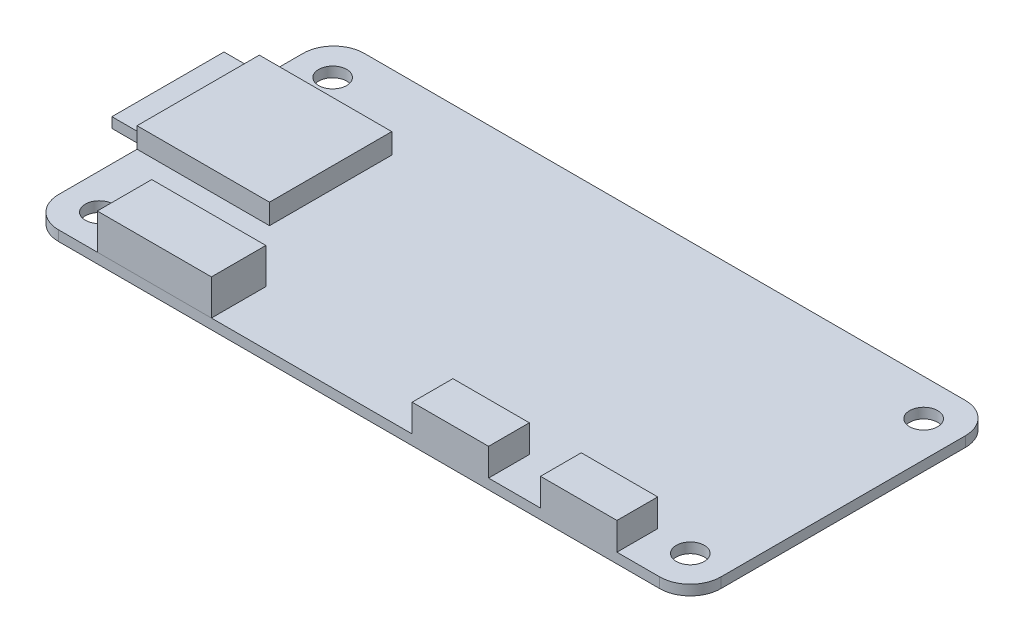
SolidWorks part; units mm, degrees
ref_plane "前视基准面" through (0, 0, 0) normal (0, 0, 1) x (1, 0, 0)
ref_plane "上视基准面" through (0, 0, 0) normal (0, 1, 0) x (1, 0, 0)
ref_plane "右视基准面" through (0, 0, 0) normal (1, 0, 0) x (0, 0, -1)
sketch "zero" plane through (0, 0, 0) normal (0, 1, 0) x (1, 0, 0)
  line L1 (-29.5, 15) -> (29.5, 15)
  line L2 (-32.5, 12) -> (-32.5, -12)
  line L3 (-29.5, -15) -> (29.5, -15)
  line L4 (32.5, 12) -> (32.5, -12)
  line L5 (-32.5, 15) -> (32.5, -15) construction
  line L6 (-32.5, -15) -> (32.5, 15) construction
  line L7 (-25.7, -15) -> (-14.5, -15)
  line L8 (-25.7, -15) -> (-25.7, -9.6569)
  line L9 (-25.7, -9.6569) -> (-14.5, -9.6569)
  line L10 (-14.5, -15) -> (-14.5, -9.6569)
  line L11 (5.2, -15) -> (12.7, -15)
  line L12 (5.2, -15) -> (5.2, -11)
  line L13 (5.2, -11) -> (12.7, -11)
  line L14 (12.7, -15) -> (12.7, -11)
  line L15 (17.8, -15) -> (25.3, -15)
  line L16 (17.8, -15) -> (17.8, -11)
  line L17 (17.8, -11) -> (25.3, -11)
  line L18 (25.3, -15) -> (25.3, -11)
  line L19 (-32.5, 7.7) -> (-19.5, 7.7)
  line L20 (-32.5, 7.7) -> (-32.5, -4.3)
  line L21 (-32.5, -4.3) -> (-19.5, -4.3)
  line L22 (-19.5, 7.7) -> (-19.5, -4.3)
  line L23 (-25.5, 14) -> (25.5, 14)
  line L24 (-25.5, 14) -> (-25.5, 8.8)
  line L25 (-25.5, 8.8) -> (25.5, 8.8)
  line L26 (25.5, 14) -> (25.5, 8.8)
  line L27 (-19.5, 7.2329) -> (-35.5, 7.2329)
  line L28 (-19.5, 7.2329) -> (-19.5, -3.7671)
  line L29 (-19.5, -3.7671) -> (-35.5, -3.7671)
  line L30 (-35.5, 7.2329) -> (-35.5, -3.7671)
  arc A0 (29.5, -15) -> (32.5, -12) centre (29.5, -12) ccw
  arc A1 (29.5, 15) -> (32.5, 12) centre (29.5, 12) cw
  arc A2 (-32.5, -12) -> (-29.5, -15) centre (-29.5, -12) ccw
  arc A3 (-29.5, 15) -> (-32.5, 12) centre (-29.5, 12) ccw
  circle A4 centre (-29, 11.4) radius 3
  circle A5 centre (-29, -11.5) radius 3
  circle A6 centre (29, 11.4) radius 3
  circle A7 centre (29, -11.5) radius 3
  circle A8 centre (-29, 11.4) radius 1.375
  circle A9 centre (-29, -11.5) radius 1.375
  circle A10 centre (29, -11.5) radius 1.375
  circle A11 centre (29, 11.4) radius 1.375
  point P0 (0, 0)
  dimension "D3" = 3
  dimension "D4" = 6
  dimension "D9" = 2.75
  dimension "D1" = 65
  dimension "D2" = 30
  dimension "D5" = 3.6
  dimension "D6" = 3.5
  dimension "D7" = 3.5
  dimension "D8" = 3.5
  dimension "D10" = 12
  dimension "D11" = 7.3
  dimension "D12" = 13
  dimension "D13" = 11.2
  dimension "D14" = 6.8
  dimension "D15" = 19.7
  dimension "D16" = 7.5
  dimension "D17" = 7.5
  dimension "D18" = 5.1
  dimension "D19" = 4
  dimension "D20" = 5.2
  dimension "D21" = 7
  dimension "D22" = 7
  dimension "D23" = 1
  dimension "D24" = 11
  dimension "D25" = 16
sketch "sugar" plane through (0, 0, 0) normal (0, 1, 0) x (1, 0, 0)
  line L1 (-29.5, 15) -> (29.5, 15)
  line L2 (-32.5, 12) -> (-32.5, -12)
  line L3 (-29.5, -15) -> (29.5, -15)
  line L4 (32.5, 12) -> (32.5, -12)
  line L5 (-32.5, 15) -> (32.5, -15) construction
  line L6 (-32.5, -15) -> (32.5, 15) construction
  line L7 (23.5, -11.5) -> (19.5, -11.5)
  line L8 (23.5, -11.5) -> (23.5, -13.9082)
  line L9 (23.5, -13.9082) -> (19.5, -13.9082)
  line L10 (19.5, -11.5) -> (19.5, -13.9082)
  line L11 (16, -11.0071) -> (8.5, -11.0071)
  line L12 (16, -11.0071) -> (16, -15)
  line L13 (16, -15) -> (8.5, -15)
  line L14 (8.5, -11.0071) -> (8.5, -15)
  line L15 (20.5, -13.9082) -> (22.5, -13.9082)
  line L16 (20.5, -13.9082) -> (20.5, -14.8173)
  line L17 (20.5, -14.8173) -> (22.5, -14.8173)
  line L18 (22.5, -13.9082) -> (22.5, -14.8173)
  arc A0 (29.5, 15) -> (32.5, 12) centre (29.5, 12) cw
  arc A1 (29.5, -15) -> (32.5, -12) centre (29.5, -12) ccw
  arc A2 (-32.5, -12) -> (-29.5, -15) centre (-29.5, -12) ccw
  arc A3 (-29.5, 15) -> (-32.5, 12) centre (-29.5, 12) ccw
  circle A4 centre (-29, 11.4) radius 3
  circle A5 centre (-29, 11.4) radius 1.375
  circle A6 centre (-29, -11.5) radius 3
  circle A7 centre (-29, -11.5) radius 1.375
  circle A8 centre (29, 11.4) radius 3
  circle A9 centre (29, 11.4) radius 1.375
  circle A10 centre (29, -11.5) radius 3
  circle A11 centre (29, -11.5) radius 1.375
  dimension "D3" = 3
  dimension "D1" = 65
  dimension "D2" = 30
  dimension "D4" = 9
  dimension "D5" = 4
  dimension "D6" = 3.5
  dimension "D7" = 7.5
  dimension "D8" = 2
  dimension "D9" = 1
sketch "草图1" plane through (0, 0, 0) normal (0, 1, 0) x (1, 0, 0)
  line L4 (-32.5, 12) -> (-32.5, -12)
  line L5 (-29.5, -15) -> (29.5, -15)
  line L6 (32.5, -12) -> (32.5, 12)
  line L7 (29.5, 15) -> (-29.5, 15)
  line L8 (-32.5, 12) -> (-32.5, -12)
  line L9 (-29.5, -15) -> (29.5, -15)
  line L10 (32.5, -12) -> (32.5, 12)
  line L11 (29.5, 15) -> (-29.5, 15)
  circle A1 centre (29, 11.4) radius 1.375
  circle A2 centre (29, 11.4) radius 1.375
  circle A3 centre (29, -11.5) radius 1.375
  circle A4 centre (29, -11.5) radius 1.375
  circle A5 centre (-29, -11.5) radius 1.375
  circle A6 centre (-29, -11.5) radius 1.375
  circle A7 centre (-29, 11.4) radius 1.375
  circle A8 centre (-29, 11.4) radius 1.375
  arc A20 (-32.5, -12) -> (-29.5, -15) centre (-29.5, -12) ccw
  arc A21 (29.5, -15) -> (32.5, -12) centre (29.5, -12) ccw
  arc A22 (32.5, 12) -> (29.5, 15) centre (29.5, 12) ccw
  arc A23 (-29.5, 15) -> (-32.5, 12) centre (-29.5, 12) ccw
  arc A24 (-32.5, -12) -> (-29.5, -15) centre (-29.5, -12) ccw
  arc A25 (29.5, -15) -> (32.5, -12) centre (29.5, -12) ccw
  arc A26 (32.5, 12) -> (29.5, 15) centre (29.5, 12) ccw
  arc A27 (-29.5, 15) -> (-32.5, 12) centre (-29.5, 12) ccw
  dimension "D1" = 0
  dimension "D2" = 0
  dimension "D3" = 0
  dimension "D4" = 0
  dimension "D9" = 0
extrude "凸台-拉伸1" add sketch "草图1" along normal blind 1
ref_plane "基准面1" through (0, 1, 0) normal (0, 1, 0) x (1, 0, 0)
sketch "草图2" plane through (0, 1, 0) normal (0, 1, 0) x (1, 0, 0)
  line L20 (17.8, -15) -> (25.3, -15)
  line L21 (25.3, -15) -> (25.3, -11)
  line L22 (25.3, -11) -> (17.8, -11)
  line L23 (17.8, -11) -> (17.8, -15)
  line L24 (17.8, -15) -> (25.3, -15)
  line L25 (25.3, -15) -> (25.3, -11)
  line L26 (25.3, -11) -> (17.8, -11)
  line L27 (17.8, -11) -> (17.8, -15)
  line L28 (5.2, -15) -> (12.7, -15)
  line L29 (12.7, -15) -> (12.7, -11)
  line L30 (12.7, -11) -> (5.2, -11)
  line L31 (5.2, -11) -> (5.2, -15)
  line L32 (5.2, -15) -> (12.7, -15)
  line L33 (12.7, -15) -> (12.7, -11)
  line L34 (12.7, -11) -> (5.2, -11)
  line L35 (5.2, -11) -> (5.2, -15)
  dimension "D11" = 0
  dimension "D12" = 0
extrude "凸台-拉伸2" add sketch "草图2" along normal blind 2.7
sketch "草图3" plane through (0, 1, 0) normal (0, 1, 0) x (1, 0, 0)
  line L36 (-25.7, -15) -> (-14.5, -15)
  line L37 (-25.7, -9.6569) -> (-25.7, -15)
  line L38 (-14.5, -9.6569) -> (-25.7, -9.6569)
  line L39 (-14.5, -15) -> (-14.5, -9.6569)
  line L40 (-25.7, -15) -> (-14.5, -15)
  line L41 (-25.7, -9.6569) -> (-25.7, -15)
  line L42 (-14.5, -9.6569) -> (-25.7, -9.6569)
  line L43 (-14.5, -15) -> (-14.5, -9.6569)
  dimension "D13" = 0
extrude "凸台-拉伸3" add sketch "草图3" along normal blind 3.5 separate body
sketch "草图4" plane through (0, 1, 0) normal (0, 1, 0) x (1, 0, 0)
  line L12 (-19.5, 7.7) -> (-32.5, 7.7)
  line L13 (-19.5, -4.3) -> (-19.5, 7.7)
  line L14 (-32.5, -4.3) -> (-19.5, -4.3)
  line L15 (-32.5, 7.7) -> (-32.5, -4.3)
  line L16 (-19.5, 7.7) -> (-32.5, 7.7)
  line L17 (-19.5, -4.3) -> (-19.5, 7.7)
  line L18 (-32.5, -4.3) -> (-19.5, -4.3)
  line L19 (-32.5, 7.7) -> (-32.5, -4.3)
  dimension "D10" = 0
extrude "凸台-拉伸4" add sketch "草图4" along normal blind 2 separate body
sketch "草图5" plane through (0, 1, 0) normal (0, 1, 0) x (1, 0, 0)
  line L44 (-19.5, 7.2329) -> (-35.5, 7.2329)
  line L45 (-35.5, 7.2329) -> (-35.5, -3.7671)
  line L46 (-35.5, -3.7671) -> (-19.5, -3.7671)
  line L47 (-19.5, -3.7671) -> (-19.5, 7.2329)
  line L48 (-19.5, 7.2329) -> (-35.5, 7.2329)
  line L49 (-35.5, 7.2329) -> (-35.5, -3.7671)
  line L50 (-35.5, -3.7671) -> (-19.5, -3.7671)
  line L51 (-19.5, -3.7671) -> (-19.5, 7.2329)
  dimension "D14" = 0
extrude "凸台-拉伸5" add sketch "草图5" along normal blind 1
